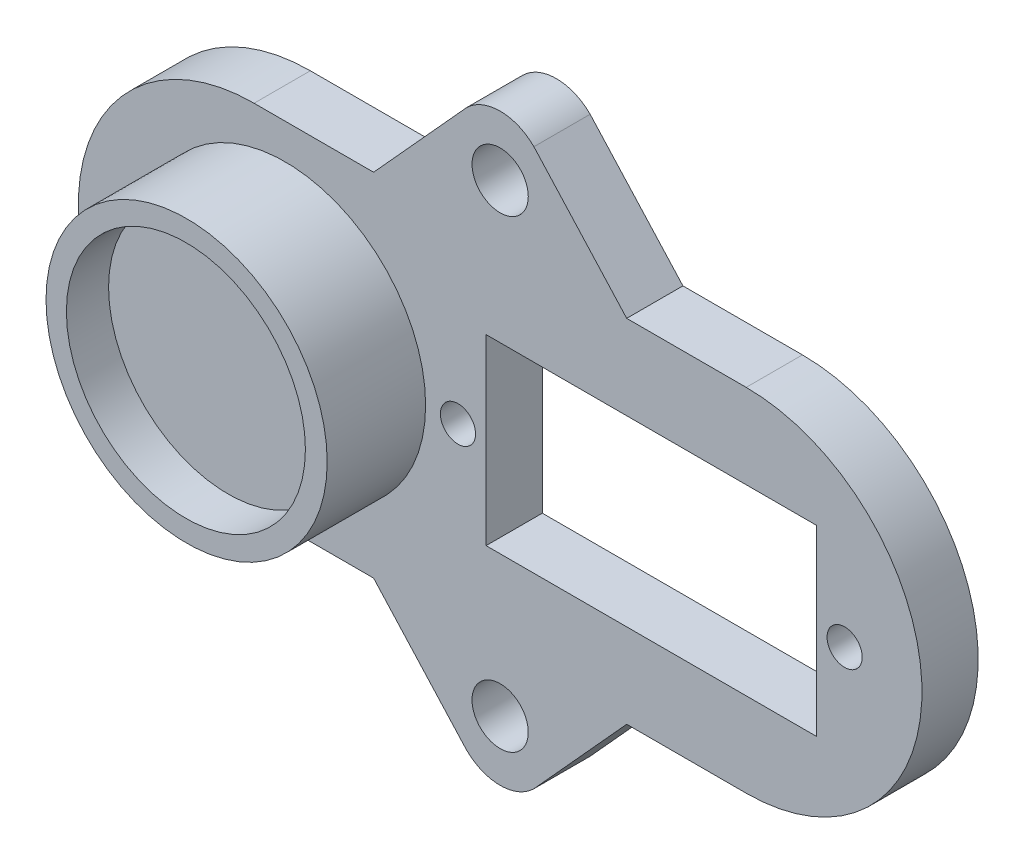
SolidWorks part; units mm, degrees
ref_plane "Front" through (0, 0, 0) normal (0, 0, 1) x (1, 0, 0)
ref_plane "Top" through (0, 0, 0) normal (0, 1, 0) x (1, 0, 0)
ref_plane "Right" through (0, 0, 0) normal (1, 0, 0) x (0, 0, -1)
sketch "Sketch1" plane through (0, 0, 0) normal (0, 0, 1) x (1, 0, 0)
  line L0 (-9, 12.5) -> (-2.401, 19.7724)
  line L1 (-17.5, 12.5) -> (-9, 12.5)
  line L5 (2.401, 19.7724) -> (9, 12.5)
  line L6 (9, 12.5) -> (17.5, 12.5)
  line L7 (-52.4135, 0) -> (76.2531, 0) construction
  line L12 (9, -12.5) -> (17.5, -12.5)
  line L13 (2.401, -19.7724) -> (9, -12.5)
  line L14 (-17.5, -12.5) -> (-9, -12.5)
  line L15 (-9, -12.5) -> (-2.401, -19.7724)
  line L19 (0, 44.7347) -> (0, -34.4115) construction
  line L24 (-1, 6.5) -> (22.5, 6.5)
  line L25 (-1, 6.5) -> (-1, -6.5)
  line L26 (-1, -6.5) -> (22.5, -6.5)
  line L27 (22.5, 6.5) -> (22.5, -6.5)
  circle A2 centre (0, 16.5) radius 2
  arc A4 (-2.401, 19.7724) -> (2.401, 19.7724) centre (0, 17.3714) cw
  arc A5 (-2.401, -19.7724) -> (2.401, -19.7724) centre (0, -17.3714) ccw
  circle A6 centre (0, -16.5) radius 2
  arc A11 (17.5, -12.5) -> (17.5, 12.5) centre (17.5, 0) ccw
  arc A12 (-17.5, 12.5) -> (-17.5, -12.5) centre (-17.5, 0) ccw
  circle A13 centre (-3, 0) radius 1.25
  circle A14 centre (24.5, 0) radius 1.25
  point P32 (-1, 0)
  dimension "D3" = 17.5
  dimension "D4" = 17.5
  dimension "D9" = 4
  dimension "D10" = 13
  dimension "D5" = 2.5
  dimension "D6" = 27.5
  dimension "D2" = 12.5
  dimension "D1" = 2.5
  dimension "D7" = 3
  dimension "D8" = 23.5
  dimension "D11" = 2
extrude "Boss-Extrude1" add sketch "Sketch1" along normal blind 4
sketch "Sketch3" plane through (0, 0, 4) normal (0, 0, 1) x (1, 0, 0)
  circle A0 centre (-15.3, 0) radius 10
  dimension "D1" = 20
  dimension "D2" = 15.3
extrude "Boss-Extrude2" add sketch "Sketch3" along normal blind 7
sketch "Sketch4" plane through (0, 0, 11) normal (0, 0, 1) x (1, 0, 0)
  circle A0 centre (-15.35, 0) radius 8.5
  dimension "D1" = 17
extrude "Cut-Extrude1" cut sketch "Sketch4" against normal blind 3
